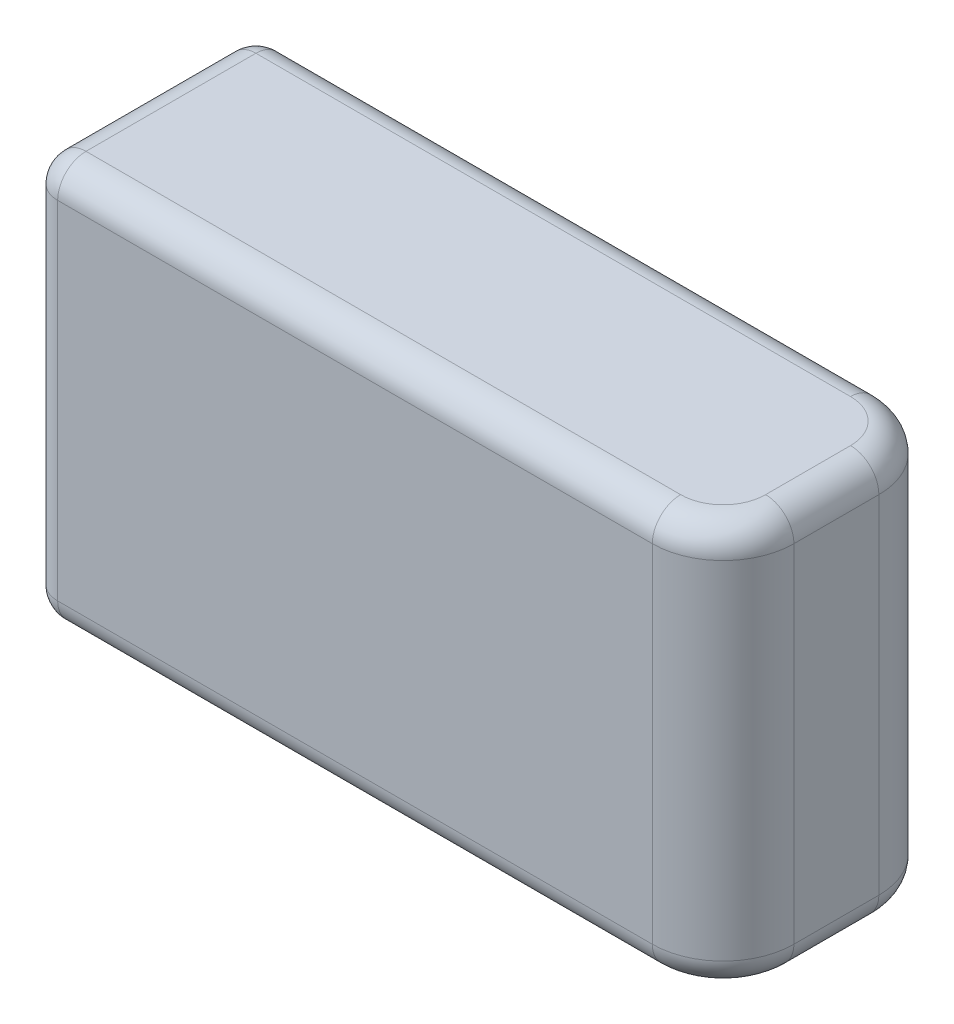
SolidWorks part; units mm, degrees
ref_plane "Front Plane" through (0, 0, 0) normal (0, 0, 1) x (1, 0, 0)
ref_plane "Top Plane" through (0, 0, 0) normal (0, 1, 0) x (1, 0, 0)
ref_plane "Right Plane" through (0, 0, 0) normal (1, 0, 0) x (0, 0, -1)
sketch "Sketch1" plane through (0, 0, 0) normal (0, 0, 1) x (1, 0, 0)
  line L0 (-24.5, -14.25) -> (-24.5, -16.25)
  line L1 (-24.5, 14.25) -> (24.5, 14.25)
  line L2 (-24.5, 14.25) -> (-24.5, -14.25)
  line L3 (-24.5, -14.25) -> (24.5, -14.25)
  line L4 (24.5, 14.25) -> (24.5, -14.25)
  line L5 (0, -14.25) -> (0, 14.25) construction
  line L6 (-24.5, 0) -> (24.5, 0) construction
  line L7 (-24.5, -16.25) -> (-17, -16.25)
  line L8 (-17, -16.25) -> (-17, 16.25)
  line L9 (-17, 16.25) -> (-24.5, 16.25)
  line L10 (-24.5, 16.25) -> (-24.5, 14.25)
  point P61 (0, 0)
  dimension "D1" = 28.5
  dimension "D2" = 49
  dimension "D3" = 7.5
  dimension "D4" = 2
  dimension "D5" = 2
extrude "Boss-Extrude1" add sketch "Sketch1" along normal blind 16 contours L8 L3 L4 L1 | L3 L8 L1 L2
fillet "Fillet2" radius 5 2 edges at (24.5, 0, 0) (24.5, 0, 16)
fillet "Fillet3" radius 2 14 edges at (-2.5, -14.25, 16) (23.0355, -14.25, 14.5355) (24.5, -14.25, 8) (23.0355, -14.25, 1.4645) (-2.5, 14.25, 16) (23.0355, 14.25, 14.5355) (24.5, 14.25, 8) (23.0355, 14.25, 1.4645) (-24.5, 14.25, 8) (-24.5, 0, 0) (-24.5, 0, 16) (-24.5, -14.25, 8) (-2.5, -14.25, 0) (-2.5, 14.25, 0)
